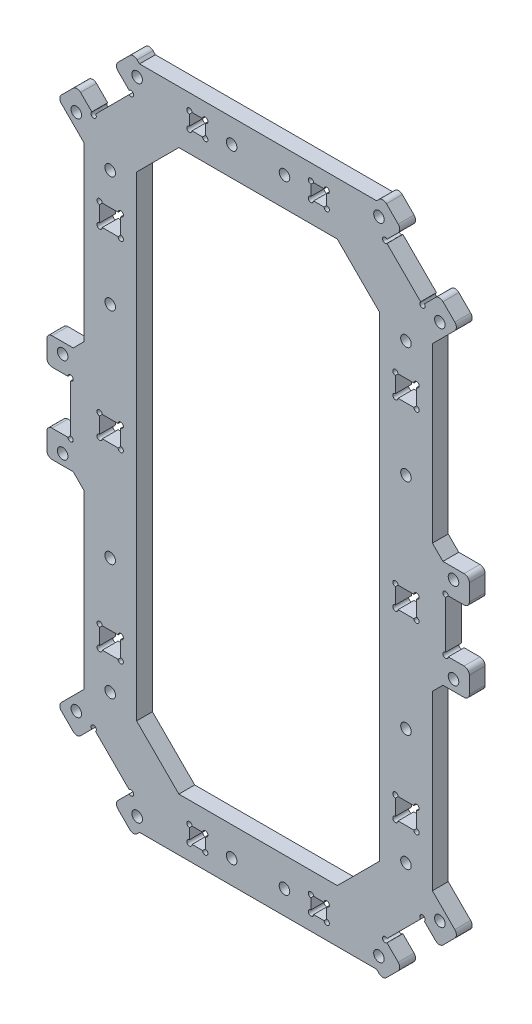
SolidWorks part; units mm, degrees
ref_plane "Front Plane" through (0, 0, 0) normal (0, 0, 1) x (1, 0, 0)
ref_plane "Top Plane" through (0, 0, 0) normal (0, 1, 0) x (1, 0, 0)
ref_plane "Right Plane" through (0, 0, 0) normal (1, 0, 0) x (0, 0, -1)
sketch "Sketch1" plane through (0, 0, 0) normal (0, 0, 1) x (1, 0, 0)
  line L0 (-44.891, 51.3771) -> (21.109, 51.3771)
  line L1 (-44.891, 51.3771) -> (-44.891, -74.6229)
  line L2 (-44.891, -74.6229) -> (21.109, -74.6229)
  line L3 (21.109, 51.3771) -> (21.109, -74.6229)
  line L6 (23.609, -11.6229) -> (23.609, -6.6229)
  line L11 (23.609, -6.6229) -> (28.109, -6.6229)
  line L12 (15.3461, 48.8895) -> (10.3964, 43.9398)
  line L17 (21.109, -11.6229) -> (-44.891, -11.6229)
  line L18 (-11.891, 51.3771) -> (-11.891, -74.6229)
  line L92 (22.4172, 41.8185) -> (17.4674, 36.8687)
  line L166 (14.609, 25.0271) -> (17.609, 25.0271)
  line L167 (14.109, 24.5271) -> (14.109, 21.5271)
  line L168 (14.609, 21.0271) -> (17.609, 21.0271)
  line L169 (18.109, 24.5271) -> (18.109, 21.5271)
  line L170 (14.609, -9.6229) -> (17.609, -9.6229)
  line L171 (14.109, -11.6229) -> (18.109, -11.6229)
  line L172 (18.109, -10.1229) -> (18.109, -13.1229)
  line L173 (-1.391, 48.3771) -> (0.609, 48.3771)
  line L174 (-1.891, 47.8771) -> (-1.891, 45.8771)
  line L175 (-1.391, 45.3771) -> (0.609, 45.3771)
  line L176 (1.109, 47.8771) -> (1.109, 45.8771)
  line L177 (-1.891, 46.8771) -> (-11.891, 46.8771)
  line L180 (-44.891, 51.3771) -> (21.109, 51.3771)
  line L188 (-37.891, -10.1229) -> (-37.891, -13.1229)
  line L189 (-37.891, -11.6229) -> (-41.891, -11.6229)
  line L190 (-41.891, -10.1229) -> (-41.891, -13.1229)
  line L191 (-38.391, -9.6229) -> (-41.391, -9.6229)
  line L252 (-44.891, -74.6229) -> (21.109, -74.6229)
  line L289 (-37.891, 24.5271) -> (-37.891, 21.5271)
  line L290 (-38.391, 25.0271) -> (-41.391, 25.0271)
  line L291 (-41.891, 24.5271) -> (-41.891, 21.5271)
  line L292 (-38.391, 21.0271) -> (-41.391, 21.0271)
  line L333 (-22.391, 48.3771) -> (-24.391, 48.3771)
  line L334 (-24.891, 47.8771) -> (-24.891, 45.8771)
  line L336 (-21.891, 47.8771) -> (-21.891, 45.8771)
  line L337 (-24.391, 45.3771) -> (-22.391, 45.3771)
  line L344 (-38.391, -13.6229) -> (-41.391, -13.6229)
  line L345 (14.609, -13.6229) -> (17.609, -13.6229)
  line L502 (14.109, -47.7729) -> (14.109, -44.7729)
  line L503 (14.609, -48.2729) -> (17.609, -48.2729)
  line L504 (18.109, -47.7729) -> (18.109, -44.7729)
  line L505 (14.609, -44.2729) -> (17.609, -44.2729)
  line L542 (-38.391, -48.2729) -> (-41.391, -48.2729)
  line L543 (-41.891, -47.7729) -> (-41.891, -44.7729)
  line L544 (-38.391, -44.2729) -> (-41.391, -44.2729)
  line L545 (-37.891, -47.7729) -> (-37.891, -44.7729)
  line L624 (-1.391, -71.6229) -> (0.609, -71.6229)
  line L625 (1.109, -71.1229) -> (1.109, -69.1229)
  line L626 (-1.391, -68.6229) -> (0.609, -68.6229)
  line L627 (-1.891, -71.1229) -> (-1.891, -69.1229)
  line L628 (-24.391, -68.6229) -> (-22.391, -68.6229)
  line L629 (-24.891, -71.1229) -> (-24.891, -69.1229)
  line L630 (-22.391, -71.6229) -> (-24.391, -71.6229)
  line L631 (-21.891, -71.1229) -> (-21.891, -69.1229)
  line L632 (14.109, -10.1229) -> (14.109, -13.1229)
  line L633 (11.7045, 52.5311) -> (6.7548, 47.5814)
  line L634 (11.7045, 52.5311) -> (26.0588, 38.1769)
  line L635 (26.0588, 38.1769) -> (21.109, 33.2271)
  line L636 (6.7548, 47.5814) -> (21.109, 33.2271)
  line L641 (18.8816, 45.354) -> (13.9319, 40.4043)
  line L642 (-11.891, 41.3771) -> (11.109, 41.3771)
  line L643 (12.1641, 45.7076) -> (19.2352, 38.6365)
  line L644 (11.109, 41.3771) -> (11.109, -11.6229)
  line L659 (21.109, -1.4729) -> (28.109, -1.4729)
  line L660 (21.109, -1.4729) -> (21.109, -11.6229)
  line L661 (21.109, -11.6229) -> (28.109, -11.6229)
  line L662 (28.109, -1.4729) -> (28.109, -11.6229)
  circle A2 centre (25.109, -3.4729) radius 1
  arc A13 (18.109, 24.5271) -> (17.609, 25.0271) centre (18.109, 25.0271) ccw
  arc A14 (14.609, 25.0271) -> (14.109, 24.5271) centre (14.109, 25.0271) ccw
  arc A15 (14.109, 21.5271) -> (14.609, 21.0271) centre (14.109, 21.0271) ccw
  arc A16 (17.609, 21.0271) -> (18.109, 21.5271) centre (18.109, 21.0271) ccw
  arc A17 (18.109, -10.1229) -> (17.609, -9.6229) centre (18.109, -9.6229) ccw
  arc A18 (14.609, -9.6229) -> (14.109, -10.1229) centre (14.109, -9.6229) ccw
  arc A19 (1.109, 47.8771) -> (0.609, 48.3771) centre (1.109, 48.3771) ccw
  arc A20 (-1.391, 48.3771) -> (-1.891, 47.8771) centre (-1.891, 48.3771) ccw
  arc A21 (-1.891, 45.8771) -> (-1.391, 45.3771) centre (-1.891, 45.3771) ccw
  arc A22 (0.609, 45.3771) -> (1.109, 45.8771) centre (1.109, 45.3771) ccw
  circle A23 centre (-6.891, 46.8771) radius 1
  arc A24 (-38.391, -9.6229) -> (-37.891, -10.1229) centre (-37.891, -9.6229) cw
  arc A25 (-41.891, -10.1229) -> (-41.391, -9.6229) centre (-41.891, -9.6229) cw
  arc A32 (-38.391, 25.0271) -> (-37.891, 24.5271) centre (-37.891, 25.0271) cw
  arc A33 (-41.891, 24.5271) -> (-41.391, 25.0271) centre (-41.891, 25.0271) cw
  arc A34 (-41.391, 21.0271) -> (-41.891, 21.5271) centre (-41.891, 21.0271) cw
  arc A35 (-37.891, 21.5271) -> (-38.391, 21.0271) centre (-37.891, 21.0271) cw
  arc A38 (-22.391, 48.3771) -> (-21.891, 47.8771) centre (-21.891, 48.3771) cw
  arc A39 (-24.891, 47.8771) -> (-24.391, 48.3771) centre (-24.891, 48.3771) cw
  arc A40 (-24.391, 45.3771) -> (-24.891, 45.8771) centre (-24.891, 45.3771) cw
  arc A41 (-21.891, 45.8771) -> (-22.391, 45.3771) centre (-21.891, 45.3771) cw
  arc A43 (-38.391, -13.6229) -> (-37.891, -13.1229) centre (-37.891, -13.6229) ccw
  arc A44 (-41.891, -13.1229) -> (-41.391, -13.6229) centre (-41.891, -13.6229) ccw
  arc A45 (14.609, -13.6229) -> (14.109, -13.1229) centre (14.109, -13.6229) cw
  arc A46 (18.109, -13.1229) -> (17.609, -13.6229) centre (18.109, -13.6229) cw
  arc A55 (14.609, -48.2729) -> (14.109, -47.7729) centre (14.109, -48.2729) cw
  arc A56 (18.109, -47.7729) -> (17.609, -48.2729) centre (18.109, -48.2729) cw
  arc A57 (17.609, -44.2729) -> (18.109, -44.7729) centre (18.109, -44.2729) cw
  arc A58 (14.109, -44.7729) -> (14.609, -44.2729) centre (14.109, -44.2729) cw
  arc A63 (-38.391, -48.2729) -> (-37.891, -47.7729) centre (-37.891, -48.2729) ccw
  arc A64 (-41.891, -47.7729) -> (-41.391, -48.2729) centre (-41.891, -48.2729) ccw
  arc A65 (-41.391, -44.2729) -> (-41.891, -44.7729) centre (-41.891, -44.2729) ccw
  arc A66 (-37.891, -44.7729) -> (-38.391, -44.2729) centre (-37.891, -44.2729) ccw
  arc A71 (-1.391, -71.6229) -> (-1.891, -71.1229) centre (-1.891, -71.6229) cw
  arc A72 (1.109, -71.1229) -> (0.609, -71.6229) centre (1.109, -71.6229) cw
  arc A73 (0.609, -68.6229) -> (1.109, -69.1229) centre (1.109, -68.6229) cw
  arc A74 (-1.891, -69.1229) -> (-1.391, -68.6229) centre (-1.891, -68.6229) cw
  circle A75 centre (-6.891, -70.1229) radius 1
  circle A76 centre (-16.891, -70.1229) radius 1
  arc A77 (-24.391, -68.6229) -> (-24.891, -69.1229) centre (-24.891, -68.6229) ccw
  arc A78 (-24.891, -71.1229) -> (-24.391, -71.6229) centre (-24.891, -71.6229) ccw
  arc A79 (-22.391, -71.6229) -> (-21.891, -71.1229) centre (-21.891, -71.6229) ccw
  arc A80 (-21.891, -69.1229) -> (-22.391, -68.6229) centre (-21.891, -68.6229) ccw
  circle A82 centre (10.9974, 48.9956) radius 1
  circle A84 centre (22.5232, 37.4698) radius 1
  circle A86 centre (16.109, 9.1671) radius 1
  circle A88 centre (12.1641, 45.7076) radius 0.5
  circle A89 centre (19.2352, 38.6365) radius 0.5
  circle A90 centre (23.609, -6.6229) radius 0.5
  circle A92 centre (16.109, 31.1671) radius 1
  point P382 (-11.891, 45.3771)
  dimension "D1" = 66
  dimension "D4" = 2
  dimension "D5" = 2
  dimension "D6" = 4
  dimension "D7" = 10.15
  dimension "D8" = 44.85
  dimension "D9" = 7
  dimension "D10" = 7
  dimension "D11" = 2.5
  dimension "D12" = 5
  dimension "D13" = 5
  dimension "D14" = 5
  dimension "D15" = 4
  dimension "D16" = 2.5
  dimension "D17" = 10
  dimension "D18" = 2
  dimension "D19" = 3
  dimension "D20" = 3
  dimension "D21" = 3
  dimension "D22" = 3
  dimension "D23" = 3
  dimension "D24" = 10
  dimension "D25" = 126
  dimension "D26" = 10
  dimension "D30" = 4
  dimension "D32" = 2
extrude "Boss-Extrude1" add sketch "Sketch1" along normal blind 3
chamfer "Chamfer1" distance 8 angle 45 1 edges at (11.109, 41.3771, 1.5)
fillet "Fillet1" radius 1 6 edges at (11.7045, 52.5311, 1.5) (15.3461, 48.8895, 1.5) (22.4172, 41.8185, 1.5) (26.0588, 38.1769, 1.5) (28.109, -1.4729, 1.5) (28.109, -6.6229, 1.5)
chamfer "Chamfer2" distance 2 angle 45 1 edges at (21.109, -1.4729, 1.5)
mirror "Mirror1" about plane through (0, -11.6229, 3) normal (0, -1, 0) of bodies 101
mirror "Mirror2" about plane through (-11.891, 0, 3) normal (1, 0, 0) of bodies 102
